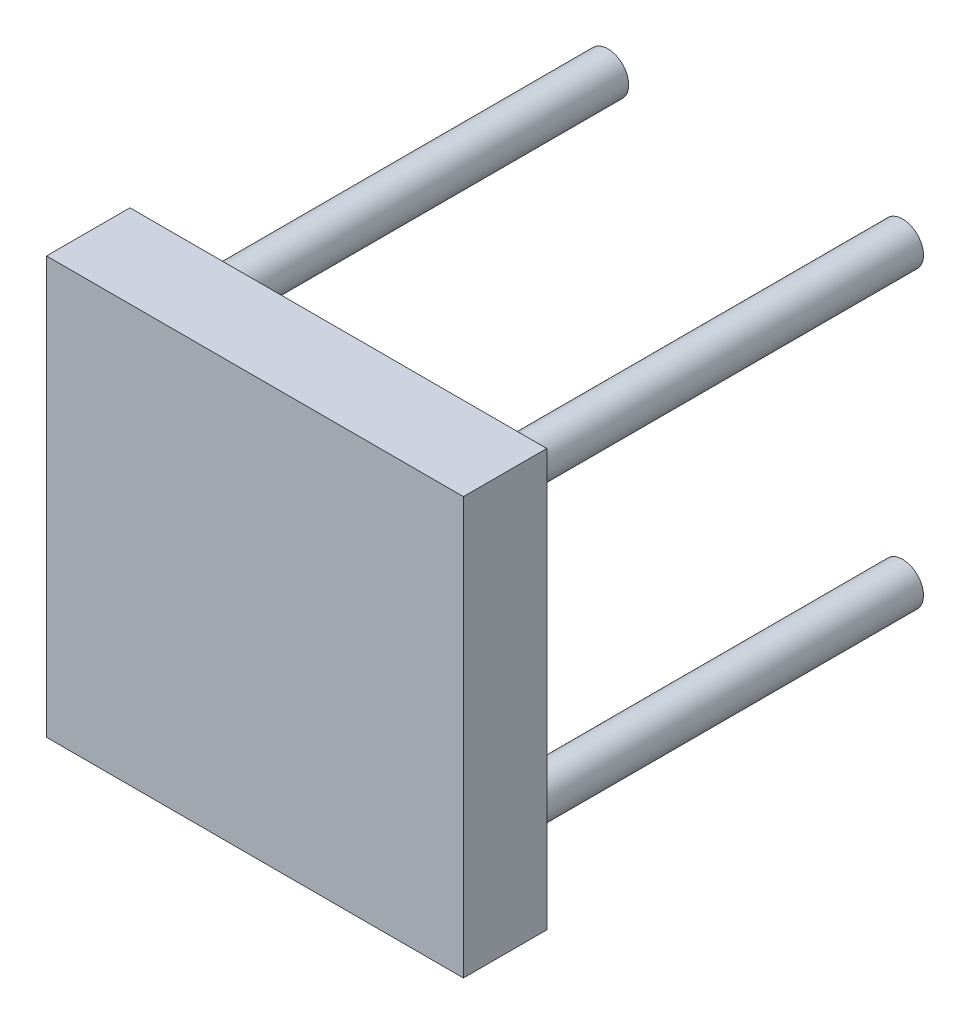
SolidWorks part; units mm, degrees
ref_plane "Front Plane" through (0, 0, 0) normal (0, 0, 1) x (1, 0, 0)
ref_plane "Top Plane" through (0, 0, 0) normal (0, 1, 0) x (1, 0, 0)
ref_plane "Right Plane" through (0, 0, 0) normal (1, 0, 0) x (0, 0, -1)
sketch "Sketch1" plane through (0, 0, 0) normal (0, 0, 1) x (1, 0, 0)
  line L1 (-0.05, -0.05) -> (0.05, -0.05)
  line L2 (-0.05, -0.05) -> (-0.05, 0.05)
  line L3 (-0.05, 0.05) -> (0.05, 0.05)
  line L4 (0.05, -0.05) -> (0.05, 0.05)
  line L5 (-0.05, -0.05) -> (0.05, 0.05) construction
  line L6 (-0.05, 0.05) -> (0.05, -0.05) construction
  point P0 (0, 0)
  dimension "D1" = 0.1
  dimension "D2" = 0.1
extrude "Boss-Extrude1" add sketch "Sketch1" against normal blind 0.02
sketch "Sketch3" plane through (0, 0, -0.02) normal (0, 0, -1) x (-1, 0, 0)
  line L0 (-0.05, 0.05) -> (0, 0) construction
  circle A0 centre (-0.0354, 0.0354) radius 0.005
  dimension "D1" = 0.01
  dimension "D2" = 0.05
extrude "Boss-Extrude2" add sketch "Sketch3" along normal blind 0.1
mirror "Mirror1" about plane through (0, 0, 0) normal (1, 0, 0) of "Boss-Extrude2"
mirror "Mirror2" about plane through (0, 0, 0) normal (0, 1, 0) of "Mirror1", "Boss-Extrude2"
equation "\"D2@Sketch1\"=\"D1@Sketch1\""
